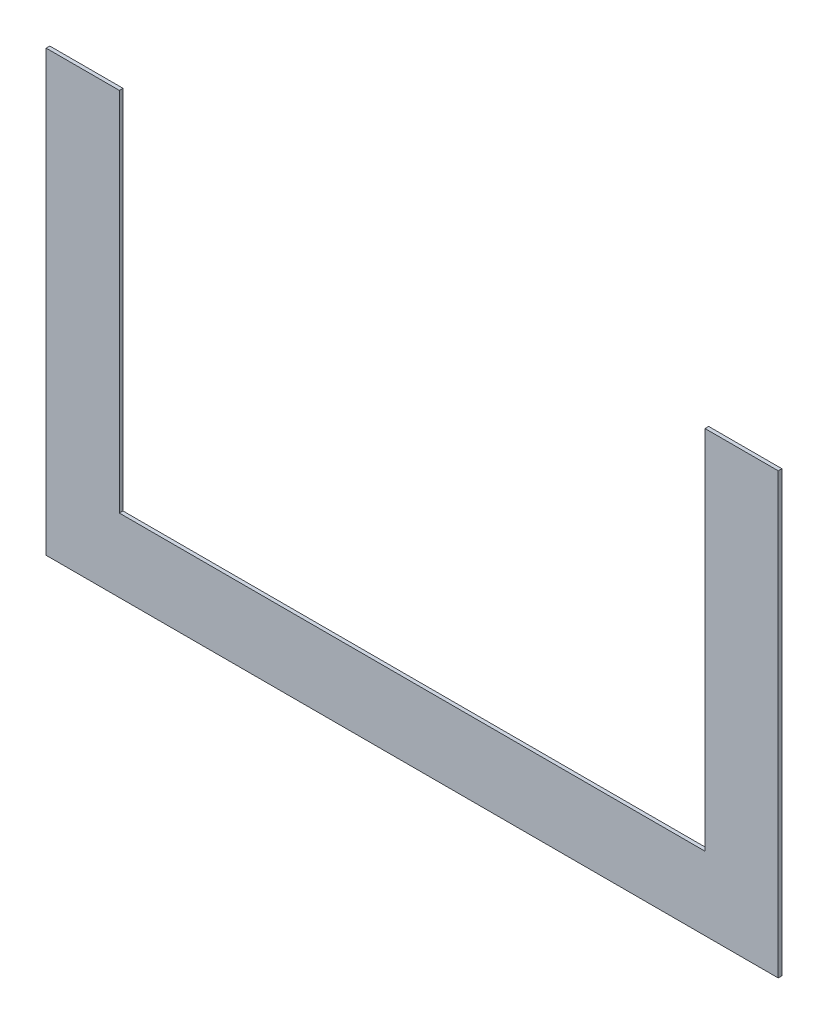
SolidWorks part; units mm, degrees
material "ABS"
ref_plane "Front Plane" through (0, 0, 0) normal (0, 0, 1) x (1, 0, 0)
ref_plane "Top Plane" through (0, 0, 0) normal (0, 1, 0) x (1, 0, 0)
ref_plane "Right Plane" through (0, 0, 0) normal (1, 0, 0) x (0, 0, -1)
sketch "Sketch2" plane through (0, 0, 0) normal (0, 0, 1) x (1, 0, 0)
  line L1 (-240.483, 47.1873) -> (165.917, 47.1873)
  line L3 (-240.483, -3.6127) -> (165.917, -3.6127)
  line L5 (-240.483, 47.1873) -> (165.917, -3.6127) construction
  line L6 (-240.483, -3.6127) -> (165.917, 47.1873) construction
  line L7 (165.917, -3.6127) -> (216.717, -3.6127)
  line L8 (-240.483, -3.6127) -> (-291.283, -3.6127)
  line L9 (-240.483, 47.1873) -> (-240.483, 301.1873)
  line L10 (-240.483, 301.1873) -> (-291.283, 301.1873)
  line L11 (-291.283, -3.6127) -> (-291.283, 301.1873)
  line L12 (-240.483, -3.6127) -> (-291.283, 301.1873) construction
  line L13 (-240.483, 301.1873) -> (-291.283, -3.6127) construction
  line L14 (165.917, 47.1873) -> (165.917, 301.1873)
  line L15 (165.917, 301.1873) -> (216.717, 301.1873)
  line L16 (216.717, -3.6127) -> (216.717, 301.1873)
  line L17 (165.917, -3.6127) -> (216.717, 301.1873) construction
  line L18 (165.917, 301.1873) -> (216.717, -3.6127) construction
  point P4 (-37.283, 21.7873)
  point P9 (-265.883, 148.7873)
  point P12 (191.317, 148.7873)
  point P13 (0, 0)
extrude "Boss-Extrude1" add sketch "Sketch2" along normal blind 2.54
